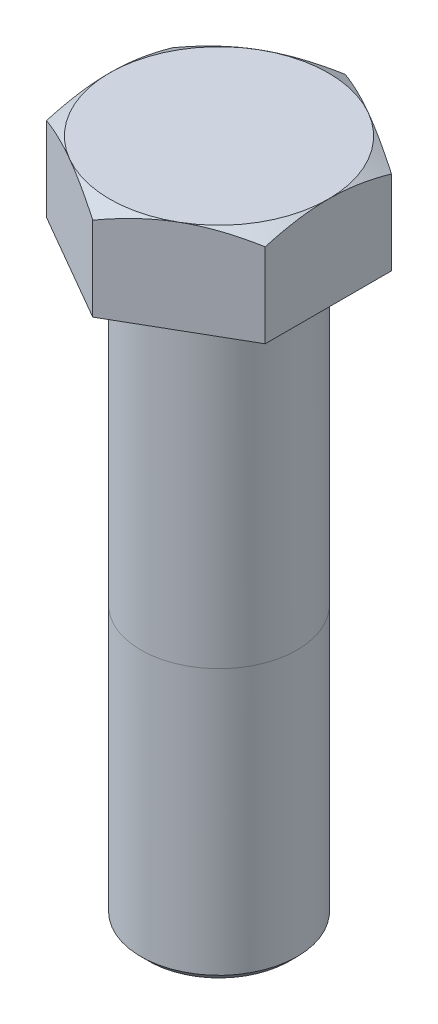
SolidWorks part; units mm, degrees
ref_plane "Front Plane" through (0, 0, 0) normal (0, 0, 1) x (1, 0, 0)
ref_plane "Top Plane" through (0, 0, 0) normal (0, 1, 0) x (1, 0, 0)
ref_plane "Right Plane" through (0, 0, 0) normal (1, 0, 0) x (0, 0, -1)
sketch "Sketch1" plane through (0, 0, 0) normal (0, 1, 0) x (1, 0, 0)
  line L1 (0, 16.1658) -> (-14, 8.0829)
  line L2 (-14, 8.0829) -> (-14, -8.0829)
  line L3 (-14, -8.0829) -> (0, -16.1658)
  line L4 (0, -16.1658) -> (14, -8.0829)
  line L5 (14, -8.0829) -> (14, 8.0829)
  line L6 (14, 8.0829) -> (0, 16.1658)
  circle A0 centre (0, 0) radius 14 construction
  point P1 (0, 0)
  dimension "D1" = 28
extrude "Boss-Extrude1" add sketch "Sketch1" along normal blind 12
sketch "Sketch2" plane through (0, 12, 0) normal (0, 1, 0) x (1, 0, 0)
  line L0 (14, 8.0829) -> (0, 16.1658) construction
  circle A0 centre (0, 0) radius 14
extrude "Cut-Extrude1" cut sketch "Sketch2" against normal blind 12 draft 60 flip side to cut
sketch "Sketch3" plane through (0, 0, 0) normal (0, -1, 0) x (1, 0, 0)
  circle A0 centre (0, 0) radius 10
  dimension "D1" = 20
extrude "Boss-Extrude2" add sketch "Sketch3" along normal blind 75
chamfer "Chamfer1" distance 1 angle 45 1 edges at (0, -75, -10)
sketch "Sketch4" plane through (0, 0, 0) normal (0, 0, 1) x (1, 0, 0)
  line L0 (-10, -40) -> (10, -40)
  line L1 (-10, 0) -> (-10, -74) construction
  line L2 (10, -74) -> (10, 0) construction
  line L4 (-10, 0) -> (10, 0) construction
  dimension "D1" = 40
split line "Split Line1"
